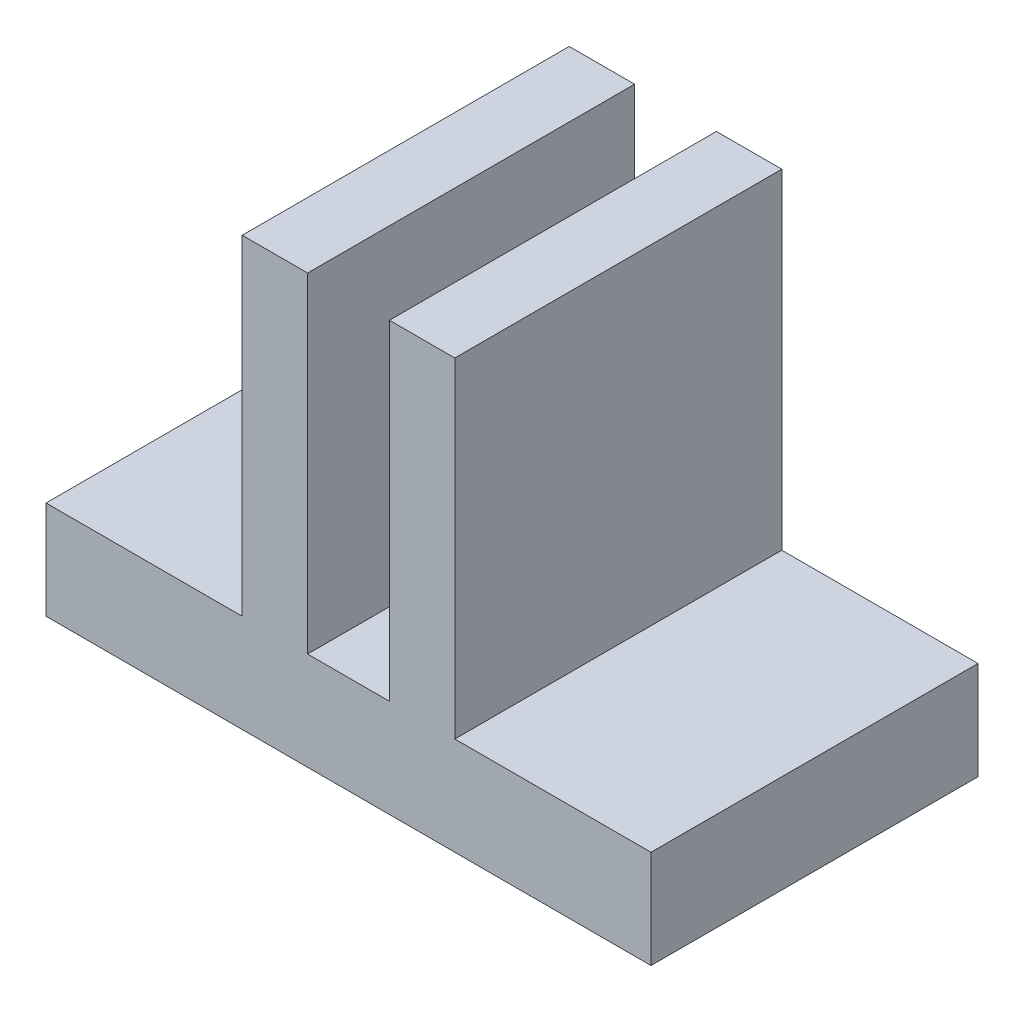
SolidWorks part; units mm, degrees
ref_plane "Front Plane" through (0, 0, 0) normal (0, 0, 1) x (1, 0, 0)
ref_plane "Top Plane" through (0, 0, 0) normal (0, 1, 0) x (1, 0, 0)
ref_plane "Right Plane" through (0, 0, 0) normal (1, 0, 0) x (0, 0, -1)
sketch "Sketch2" plane through (0, 0, 0) normal (0, 0, 1) x (1, 0, 0)
  line L0 (-48.7601, -8.3378) -> (-18.7601, -8.3378)
  line L1 (-18.7601, -8.3378) -> (-18.7601, 42.1162)
  line L2 (-18.7601, 42.1162) -> (-8.7601, 42.1162)
  line L3 (-8.7601, 42.1162) -> (-8.7601, -8.3378)
  line L4 (-8.7601, -8.3378) -> (3.7466, -8.3378)
  line L5 (3.7466, -8.3378) -> (3.7466, 42.1162)
  line L6 (3.7466, 42.1162) -> (13.7466, 42.1162)
  line L7 (13.7466, 42.1162) -> (13.7466, -8.3378)
  line L8 (13.7466, -8.3378) -> (43.7466, -8.3378)
  line L9 (43.7466, -8.3378) -> (43.7466, -23.3378)
  line L10 (43.7466, -23.3378) -> (-48.7601, -23.3378)
  line L11 (-48.7601, -23.3378) -> (-48.7601, -8.3378)
  dimension "D1" = 15
  dimension "D2" = 30
  dimension "D3" = 30
  dimension "D4" = 10
  dimension "D5" = 10
sketch3d "3DSketch1" plane through (0, 0, 0) normal (0, 0, 1) x (1, 0, 0)
extrude "Boss-Extrude2" add sketch "Sketch2" along normal blind 50
